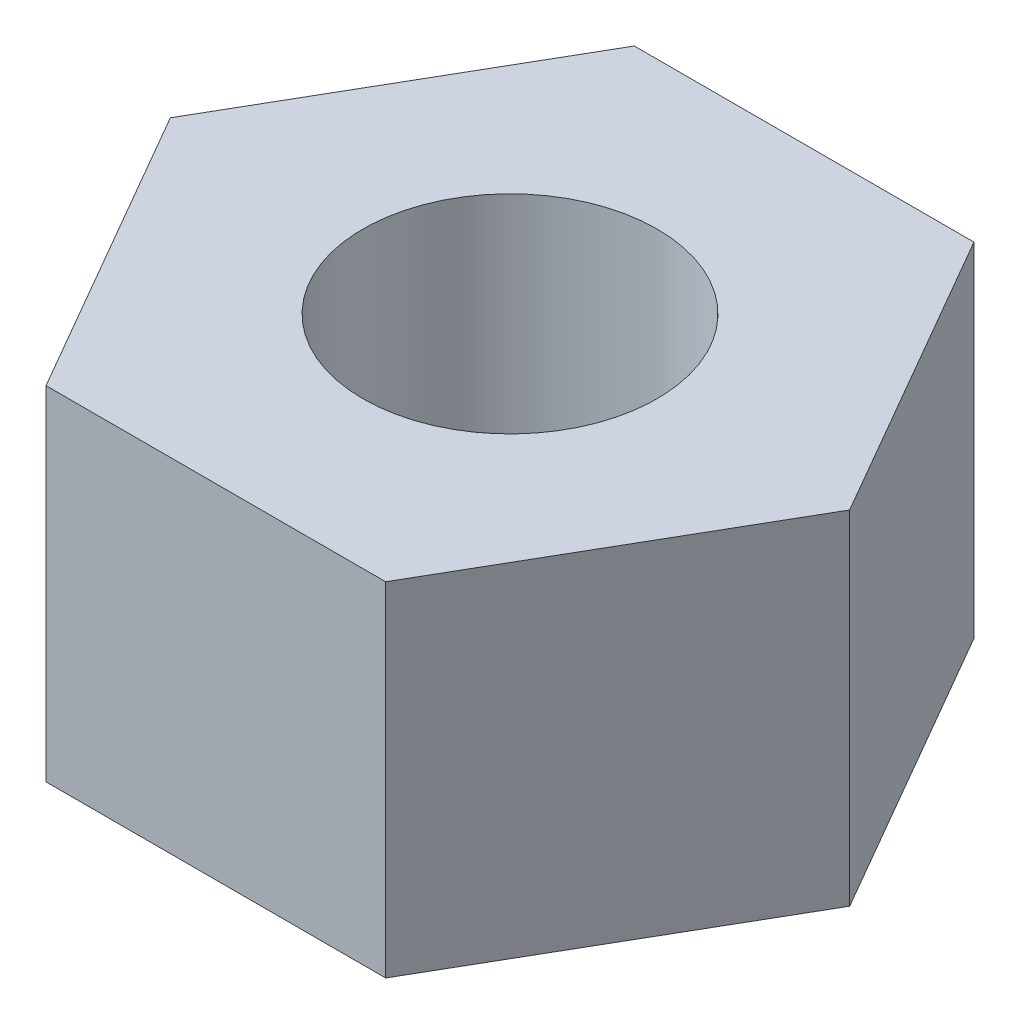
SolidWorks part; units mm, degrees
ref_plane "Front Plane" through (0, 0, 0) normal (0, 0, 1) x (1, 0, 0)
ref_plane "Top Plane" through (0, 0, 0) normal (0, 1, 0) x (1, 0, 0)
ref_plane "Right Plane" through (0, 0, 0) normal (1, 0, 0) x (0, 0, -1)
sketch "Sketch1" plane through (0, 0, 0) normal (0, 1, 0) x (1, 0, 0)
  line L1 (34.641, 0) -> (17.3205, 30)
  line L2 (17.3205, 30) -> (-17.3205, 30)
  line L3 (-17.3205, 30) -> (-34.641, 0)
  line L4 (-34.641, 0) -> (-17.3205, -30)
  line L5 (-17.3205, -30) -> (17.3205, -30)
  line L6 (17.3205, -30) -> (34.641, 0)
  circle A0 centre (0, 0) radius 30 construction
  circle A1 centre (0, 0) radius 15
  dimension "D2" = 30
  dimension "D1" = 60
extrude "Boss-Extrude1" add sketch "Sketch1" along normal blind 35
